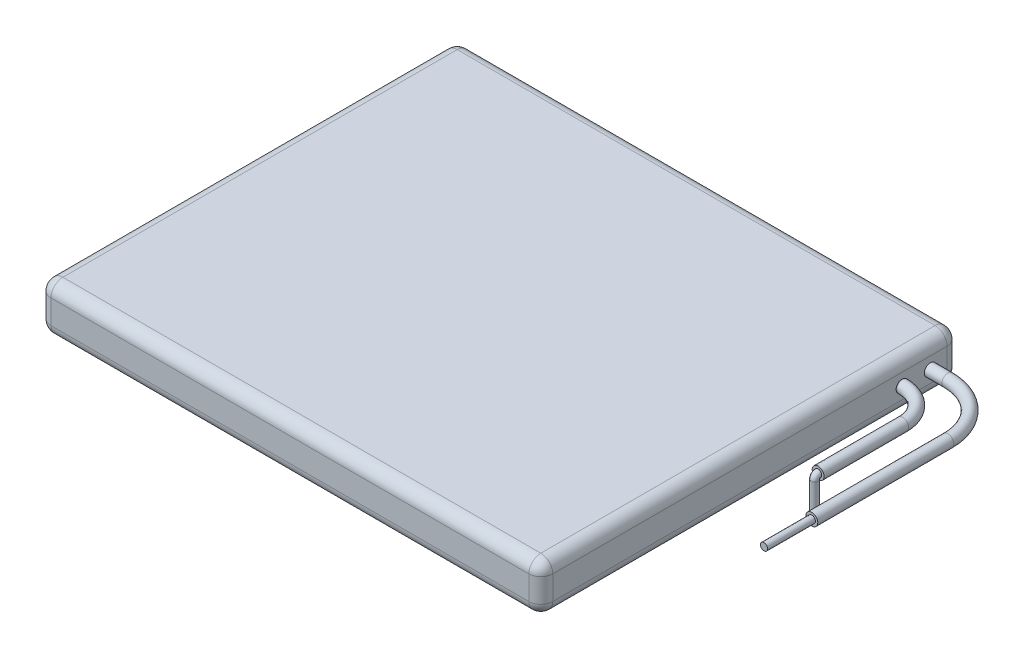
SolidWorks part; units mm, degrees
other "Camera1"
ref_plane "Front Plane" through (0, 0, 0) normal (0, 0, 1) x (1, 0, 0)
ref_plane "Top Plane" through (0, 0, 0) normal (0, 1, 0) x (1, 0, 0)
ref_plane "Right Plane" through (0, 0, 0) normal (1, 0, 0) x (0, 0, -1)
sketch "Sketch1" plane through (0, 0, 0) normal (0, 1, 0) x (1, 0, 0)
  line L1 (0, 0) -> (42, 0)
  line L2 (0, 0) -> (0, 35)
  line L3 (0, 35) -> (42, 35)
  line L4 (42, 0) -> (42, 35)
  dimension "D1" = 35
  dimension "D2" = 42
extrude "Boss-Extrude1" add sketch "Sketch1" along normal blind 4 contours L1 L4 L3 L2
fillet "Fillet1" radius 1 4 edges at (42, 2, 0) (42, 2, -35) (0, 2, -35) (0, 2, 0)
fillet "Fillet2" radius 1 16 edges at (0.2929, 0, -0.2929) (0, 0, -17.5) (0.2929, 0, -34.7071) (21, 0, -35) (41.7071, 0, -34.7071) (42, 0, -17.5) (41.7071, 0, -0.2929) (0.2929, 4, -34.7071) (0, 4, -17.5) (0.2929, 4, -0.2929) (21, 4, 0) (41.7071, 4, -0.2929) (42, 4, -17.5) (41.7071, 4, -34.7071) (21, 0, 0) (21, 4, -35)
sketch "Sketch2" plane through (42, 0, 0) normal (1, 0, 0) x (0, 0, -1)
  line L0 (1, 4) -> (34, 4) construction
  circle A0 centre (32.5988, 2) radius 0.5
  dimension "D2" = 1
  dimension "D3" = 2
sketch "Sketch4" plane through (0, 0, 0) normal (0, 1, 0) x (1, 0, 0)
  line L0 (42, 32.5988) -> (43.472, 32.5988)
  line L1 (42, 32.0988) -> (42, 33.0988) construction
  line L2 (47.8742, 28.1966) -> (47.8742, 16.8057)
  arc A1 (43.472, 32.5988) -> (47.8742, 28.1966) centre (43.472, 28.1966) cw
  point P5 (0, 0)
  point P6 (47.8467, 13.8015)
  point P7 (47.8742, 16.8057)
sweep "Sweep2" add profiles "Sketch2" path "Sketch4"
sketch "Sketch5" plane through (42, 0, 0) normal (1, 0, 0) x (0, 0, -1)
  line L0 (1, 4) -> (34, 4) construction
  circle A0 centre (30.2378, 2) radius 0.5
  dimension "D1" = 1
  dimension "D2" = 2
sketch "Sketch6" plane through (0, 0, 0) normal (0, 1, 0) x (1, 0, 0)
  line L0 (42, 30.2378) -> (42.054, 30.2378)
  line L1 (42, 29.7378) -> (42, 30.7378) construction
  line L2 (44.795, 27.4968) -> (44.795, 20.4155)
  circle A0 centre (44.795, 20.009) radius 0.4065 construction
  arc A1 (42.054, 30.2378) -> (44.795, 27.4968) centre (42.054, 27.4968) cw
sweep "Sweep3" add profiles "Sketch5" path "Sketch6"
sketch "Sketch10" plane through (0, 0, -20.4155) normal (0, 0, 1) x (1, 0, 0)
  circle A2 centre (44.795, 2) radius 0.3
  circle A3 centre (44.795, 2) radius 0.3
  dimension "D1" = 0.2
ref_plane "Plane1" through (44.8288, 0, 0) normal (1, 0, 0) x (0, 0, -1)
sketch "Sketch12" plane through (44.8288, 0, 0) normal (1, 0, 0) x (0, 0, -1)
  line L0 (20.4155, 2) -> (20.4131, 2)
  line L1 (20.4155, 2.3) -> (20.4155, 1.7) construction
  line L2 (20.1131, 1.7) -> (20.1131, -1.3447)
  arc A0 (20.4131, 2) -> (20.1131, 1.7) centre (20.4131, 1.7) ccw
  dimension "D1" = 0.3
sweep "Sweep5" add profiles "Sketch10" path "Sketch12"
sketch "Sketch13" plane through (0, 0, -16.8057) normal (0, 0, 1) x (1, 0, 0)
  circle A2 centre (47.8742, 2) radius 0.3
  circle A3 centre (47.8742, 2) radius 0.3
  dimension "D1" = 0.2
extrude "Boss-Extrude2" add sketch "Sketch13" along normal blind 4
